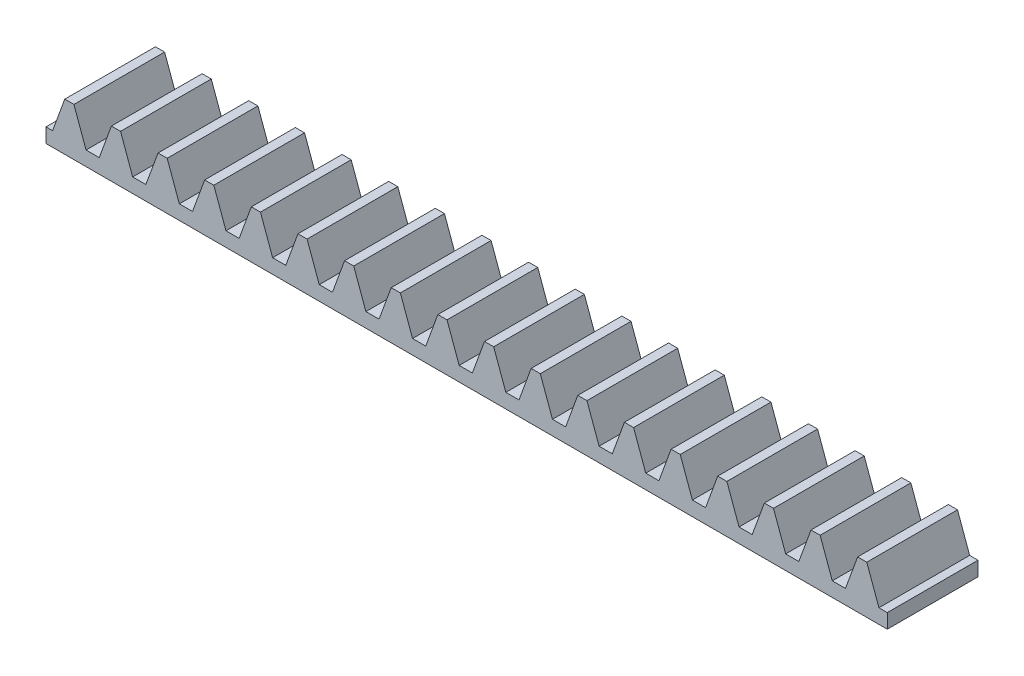
SolidWorks part; units mm, degrees
extrude "Blank" add sketch "BlankSke" against normal blind 5.5
sketch "BlankSke" plane through (0, 0, 0) normal (0, 0, 1) x (1, 0, 0)
  line L1 (0, 0) -> (51, 0)
  line L2 (0, 0) -> (0, 2.9)
  line L3 (0, 2.9) -> (51, 2.9)
  line L4 (51, 0) -> (51, 2.9)
  dimension "Length" = 51
  dimension "Blank_height" = 2.9
ref_plane "Plane1" through (0, 0, 0) normal (0, 0, 1) x (1, 0, 0)
ref_plane "Plane2" through (0, 0, 0) normal (0, 1, 0) x (1, 0, 0)
ref_plane "Plane3" through (0, 0, 0) normal (1, 0, 0) x (0, 0, -1)
other "Configuration Table"
sketch "HoldingSke" plane through (0, 0, 0) normal (0, 1, 0) x (1, 0, 0)
  line L0 (0, 0) -> (0.1546, 1.1003)
  line L1 (-15, 0) -> (100, 0) construction
  line L2 (0, 0) -> (-2.1039, 2.3779)
  line L3 (0, 0) -> (-11.863, 4.5341)
  line L4 (0, 0) -> (8.1152, 2.9537)
  line L5 (0, 0) -> (-23.7986, -8.8762)
  line L6 (0, 0) -> (-10.5278, -7.1032)
  line L9 (-71.009, 38.7566) -> (-23.0846, 56.1996)
  line L10 (-76.2, 3.2779) -> (-74.2, 3.2779)
  line L11 (0, 0) -> (-5.5, 0)
  line L12 (-76.2, 101.6) -> (-76.166, 101.6)
  line L13 (24.9733, 27.94) -> (52.9518, 28.4284)
  line L14 (24.9733, 27.94) -> (24.9743, 27.94)
  line L15 (24.9733, 27.94) -> (100.4006, 29.5858)
  circle A0 centre (0, 0) radius 19.05
  circle A1 centre (0, 0) radius 1
  circle A2 centre (0, 0) radius 12.7
  dimension "MPH" = 2
  dimension "Diameter" = 38.1
  dimension "Num_teeth" = 20
  dimension "Pitch" = 1.1111
  dimension "Show_teeth" = 998
  dimension "Thickness" = 12.7
  dimension "Ap" = 20
  dimension "Pitch_height" = 2
  dimension "Width" = 5.5
  dimension "Backlash" = 0.034
  dimension "Addendum_fac" = 1
  dimension "Dedendum_fac" = 1.25
  dimension "Clearance_fac" = 0.25
  dimension "Dedendum_add" = 0.001
  dimension "Length" = 51
  dimension "Module" = 0.9
sketch "TooCutSkeIll" plane through (0, 0, 0) normal (0, 0, 1) x (1, 0, 0)
  line L0 (-1.1278, 2.8763) -> (-0.4535, 1.0237)
  line L1 (-0.2411, 0.875) -> (0.2411, 0.875)
  line L2 (0.4535, 1.0237) -> (1.1278, 2.8763)
  line L3 (51, 2.9) -> (0, 2.9) construction
  line L4 (0, 0) -> (0, 64.897) construction
  line L5 (-13.208, 2) -> (12.954, 2) construction
  line L6 (0, 0) -> (51, 0) construction
  line L7 (0.8089, 2) -> (0.8089, 48.7463) construction
  line L8 (-0.8089, 2) -> (-0.8089, 48.7463) construction
  line L9 (1.1616, 2.9) -> (1.1616, 2.9254)
  line L10 (-1.1616, 2.9) -> (-1.1616, 2.9254)
  line L11 (-1.1616, 2.9254) -> (1.1616, 2.9254)
  arc A0 (0.2411, 0.875) -> (0.4535, 1.0237) centre (0.2411, 1.101) ccw
  arc A1 (-0.4535, 1.0237) -> (-0.2411, 0.875) centre (-0.2411, 1.101) ccw
  arc A2 (1.1616, 2.9) -> (1.1278, 2.8763) centre (1.1616, 2.864) ccw
  arc A3 (-1.1278, 2.8763) -> (-1.1616, 2.9) centre (-1.1616, 2.864) ccw
  dimension "Pitch_height" = 2
  dimension "Addendum_plus" = 0.9254
  dimension "Pressure_angle" = 20
  dimension "Gap_width" = 1.6177
  dimension "Dedendum" = 1.125
extrude "ToothCutIll" [suppressed] cut sketch "TooCutSkeIll" against normal through all
sketch "TooCutSkeSim" plane through (0, 0, 0) normal (0, 0, 1) x (1, 0, 0)
  line L0 (0.3994, 0.875) -> (-0.3994, 0.875)
  line L1 (1.1457, 2.9254) -> (0.3994, 0.875)
  line L2 (0, 17.4625) -> (0, 53.467) construction
  line L3 (1.1457, 2.9254) -> (-1.1457, 2.9254)
  line L6 (-1.1457, 2.9254) -> (-0.3994, 0.875)
  line L9 (-0.8089, 2) -> (0.8089, 2) construction
  line L10 (0, 0) -> (51, 0) construction
  line L11 (0.8089, 2) -> (0.8089, 53.467) construction
  line L12 (-0.8089, 2) -> (-0.8089, 53.467) construction
  dimension "Pitch_height" = 2
  dimension "Addendum_plus" = 0.9254
  dimension "Pressure_angle" = 20
  dimension "Gap_width" = 1.6177
  dimension "Dedendum" = 1.125
extrude "ToothCutSim" cut sketch "TooCutSkeSim" against normal through all
pattern_linear "TeethCuts" count 19 spacing 2.8274 along (1, 0, 0) of "ToothCutIll", "ToothCutSim"
equation "' \"Module@HoldingSke\" = 6.35"
equation "' \"Num_teeth@HoldingSke\" = 12"
equation "' \"Ap@HoldingSke\" =  20"
equation "' \"Ap@HoldingSke\" = 20"
equation "' \"Width@HoldingSke\" = 0.25 * 25.4"
equation "' \"Show_teeth@HoldingSke\" = 500"
equation "' \"Backlash@HoldingSke\" = 0.009 * 25.4"
equation "' \"Addendum_fac@HoldingSke\" = 1.0"
equation "' \"Dedendum_fac@HoldingSke\" = 1.25"
equation "' \"Dedendum_add@HoldingSke\" = 0.00005 * 25.4"
equation "' \"Clearance_fac@HoldingSke\" = 0.25"
equation "' \"Pitch_height@HoldingSke\" = 1 * 25.4"
equation "' \"Length@HoldingSke\" = 4.71 * 25.4"
equation "\"Pitch@HoldingSke\" = 1 / \"Module@HoldingSke\""
equation "\"MPH@HoldingSke\" = \"Dedendum_fac@HoldingSke\" / \"Pitch@HoldingSke\" + 2 * \"Dedendum_add@HoldingSke\" + 0.002 * 25.4"
equation "\"MPH@HoldingSke\" = ((sgn( \"MPH@HoldingSke\" - \"Pitch_height@HoldingSke\")+1)*( \"MPH@HoldingSke\" - \"Pitch_height@HoldingSke\"))/2 + \"Pitch_height@HoldingSke\""
equation "\"Blank_height@BlankSke\" = \"Pitch_height@HoldingSke\" + \"Addendum_fac@HoldingSke\"  / \"Pitch@HoldingSke\" "
equation "\"Length@BlankSke\" =  \"Length@HoldingSke\""
equation "\"Face_width@Blank\" = \"Width@HoldingSke\""
equation "\"Pressure_angle@TooCutSkeIll\" = \"Ap@HoldingSke\""
equation "\"Addendum_plus@TooCutSkeIll\" =  \"Addendum_fac@HoldingSke\"  / \"Pitch@HoldingSke\" + 0.001 *25.4"
equation "\"Dedendum@TooCutSkeIll\" = \"Dedendum_fac@HoldingSke\"  / \"Pitch@HoldingSke\""
equation "\"Pitch_height@TooCutSkeIll\" =  \"MPH@HoldingSke\""
equation "\"Gap_width@TooCutSkeIll\" = 3.14159265 / 2 / \"Pitch@HoldingSke\" + 6 * \"Backlash@HoldingSke\""
equation "\"Pressure_angle@TooCutSkeSim\" = \"Ap@HoldingSke\""
equation "\"Addendum_plus@TooCutSkeSim\" =  \"Addendum_fac@HoldingSke\"  / \"Pitch@HoldingSke\" + 0.001 * 25.4"
equation "\"Dedendum@TooCutSkeSim\" = \"Dedendum_fac@HoldingSke\"  / \"Pitch@HoldingSke\""
equation "\"Pitch_height@TooCutSkeSim\" =  \"MPH@HoldingSke\""
equation "\"Gap_width@TooCutSkeSim\" = 3.14159265 / 2 / \"Pitch@HoldingSke\" + 6 * \"Backlash@HoldingSke\""
equation "\"Root_fillet@TooCutSkeIll\" = \"Clearance_fac@HoldingSke\" / \"Pitch@HoldingSke\" + \"Dedendum_add@HoldingSke\""
equation "\"Break_rad@TooCutSkeIll\" = 0.02 / \"Pitch@HoldingSke\" * 2"
equation "\"Linear_pitch@TeethCuts\" = 3.14159265 / \"Pitch@HoldingSke\""
equation "\"Num_teeth@HoldingSke\" = int( ( \"Length@HoldingSke\" + 0 ) / (3.14159265 / \"Pitch@HoldingSke\")) + 0.9999  + 1"
equation " \"Num_teeth@TeethCuts\" = int( \"Show_teeth@HoldingSke\" ) + 1"
equation " \"Num_teeth@TeethCuts\" = ((sgn( \"Num_teeth@TeethCuts\" - \"Num_teeth@HoldingSke\" )-1)*( \"Num_teeth@TeethCuts\" - \"Num_teeth@HoldingSke\" ))/-2+ \"Num_teeth@HoldingSke\""
equation " \"Num_teeth@TeethCuts\" = ((sgn( \"Num_teeth@TeethCuts\" - 2.0)+1)*( \"Num_teeth@TeethCuts\" - 2.0))/2 +2.0"
